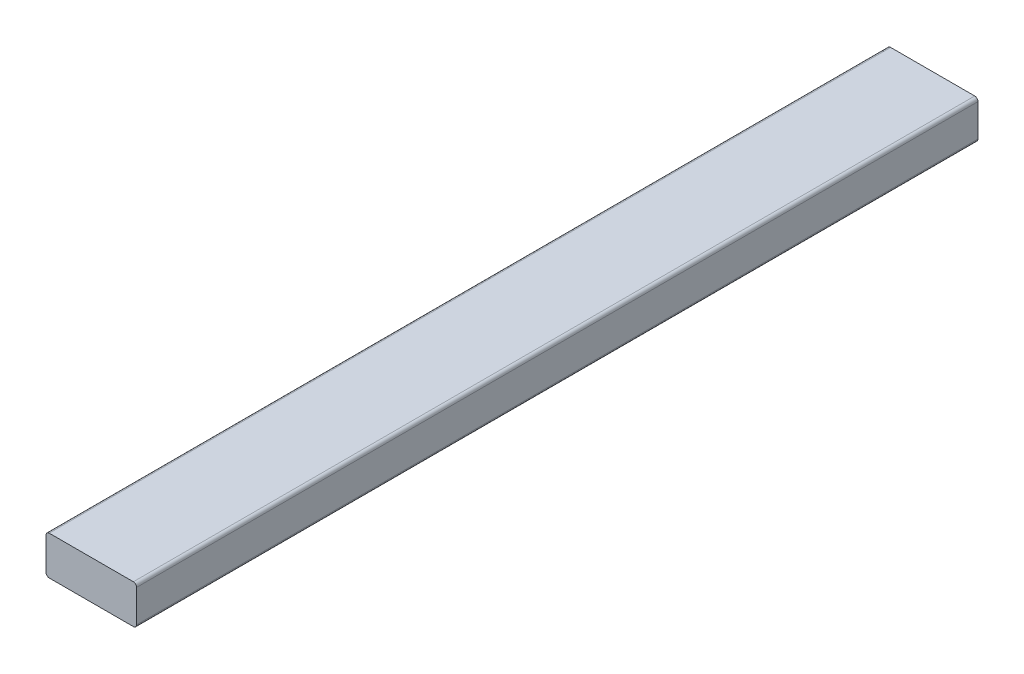
SolidWorks part; units mm, degrees
material "Pine"
ref_plane "Front Plane" through (0, 0, 0) normal (0, 0, 1) x (1, 0, 0)
ref_plane "Top Plane" through (0, 0, 0) normal (0, 1, 0) x (1, 0, 0)
ref_plane "Right Plane" through (0, 0, 0) normal (1, 0, 0) x (0, 0, -1)
sketch "Sketch1" plane through (0, 0, 0) normal (0, 0, 1) x (1, 0, 0)
  line L1 (-44.45, 19.05) -> (44.45, 19.05)
  line L2 (-44.45, 19.05) -> (-44.45, -19.05)
  line L3 (-44.45, -19.05) -> (44.45, -19.05)
  line L4 (44.45, 19.05) -> (44.45, -19.05)
  line L5 (0, -19.05) -> (0, 19.05) construction
  line L6 (-44.45, 0) -> (44.45, 0) construction
  point P0 (0, 0)
  dimension "D1" = 88.9
  dimension "D2" = 38.1
extrude "Boss-Extrude1" add sketch "Sketch1" along normal mid plane 825.5
fillet "Fillet1" radius 3.175 4 edges at (44.45, -19.05, 0) (-44.45, -19.05, 0) (-44.45, 19.05, 0) (44.45, 19.05, 0)
